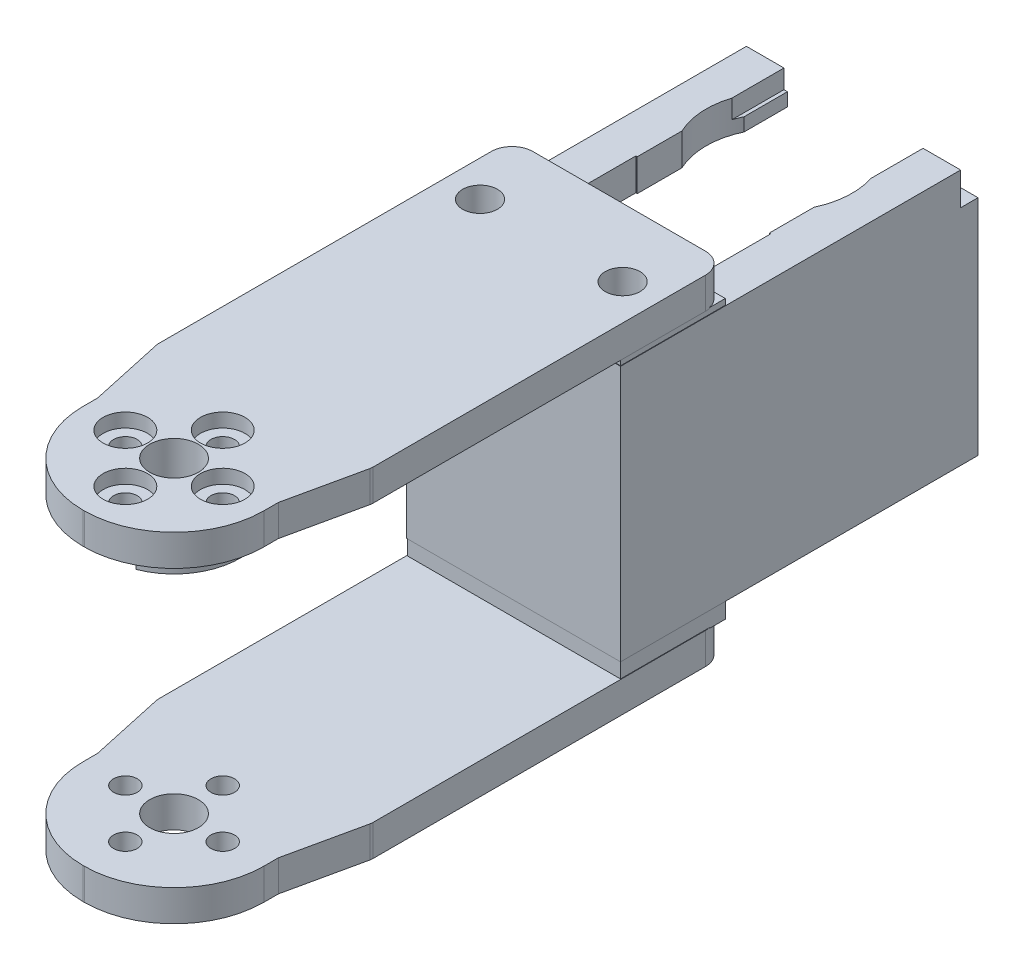
SolidWorks part; units mm, degrees
ref_plane "Front Plane" through (0, 0, 0) normal (0, 0, 1) x (1, 0, 0)
ref_plane "Top Plane" through (0, 0, 0) normal (0, 1, 0) x (1, 0, 0)
ref_plane "Right Plane" through (0, 0, 0) normal (1, 0, 0) x (0, 0, -1)
ref_plane "PY_m23_300" through (0, -23.3, 0) normal (0, 1, 0) x (1, 0, 0)
sketch "S_prism1" plane through (0, -23.3, 0) normal (0, 1, 0) x (1, 0, 0)
  line L0 (-13, 2) -> (-15.354, 12.7893)
  line L1 (-15.4, 13.2156) -> (-15.4, 61)
  line L2 (-12.4, 64) -> (12.4, 64)
  line L3 (15.4, 61) -> (15.4, 13.2156)
  line L4 (15.354, 12.7893) -> (13, 2)
  line L5 (13, 2) -> (13, -0.1)
  line L6 (0.1, -13) -> (-0.1, -13)
  line L7 (-13, -0.1) -> (-13, 2)
  arc A0 (-15.354, 12.7893) -> (-15.4, 13.2156) centre (-13.4076, 13.215) cw
  arc A1 (-15.4, 61) -> (-12.4, 64) centre (-12.3999, 60.9999) cw
  arc A2 (12.4, 64) -> (15.4, 61) centre (12.3999, 60.9999) cw
  arc A3 (15.4, 13.2156) -> (15.354, 12.7893) centre (13.4076, 13.215) cw
  arc A4 (13, -0.1) -> (0.1, -13) centre (0.1001, -0.1001) cw
  arc A5 (-0.1, -13) -> (-13, -0.1) centre (-0.1001, -0.1001) cw
extrude "Boss_1" add sketch "S_prism1" along normal blind 4.5
ref_plane "PY_p17_750" through (0, 17.75, 0) normal (0, 1, 0) x (1, 0, 0)
sketch "S_cyl2" plane through (0, 17.75, 0) normal (0, 1, 0) x (1, 0, 0)
  circle A0 centre (0, 0) radius 9.5
  dimension "D1_S_cyl2" = 19
extrude "Boss_2" add sketch "S_cyl2" along normal blind 3.2
ref_plane "PY_p20_950" through (0, 20.95, 0) normal (0, 1, 0) x (1, 0, 0)
sketch "S_prism3" plane through (0, 20.95, 0) normal (0, 1, 0) x (1, 0, 0)
  line L0 (-13, 2) -> (-15.354, 12.7893)
  line L1 (-15.4, 13.2156) -> (-15.4, 61)
  line L2 (-12.4, 64) -> (12.4, 64)
  line L3 (15.4, 61) -> (15.4, 13.2156)
  line L4 (15.354, 12.7893) -> (13, 2)
  line L5 (13, 2) -> (13, -0.1)
  line L6 (0.1, -13) -> (-0.1, -13)
  line L7 (-13, -0.1) -> (-13, 2)
  arc A0 (-15.354, 12.7893) -> (-15.4, 13.2156) centre (-13.4076, 13.215) cw
  arc A1 (-15.4, 61) -> (-12.4, 64) centre (-12.3999, 60.9999) cw
  arc A2 (12.4, 64) -> (15.4, 61) centre (12.3999, 60.9999) cw
  arc A3 (15.4, 13.2156) -> (15.354, 12.7893) centre (13.4076, 13.215) cw
  arc A4 (13, -0.1) -> (0.1, -13) centre (0.1001, -0.1001) cw
  arc A5 (-0.1, -13) -> (-13, -0.1) centre (-0.1001, -0.1001) cw
extrude "Boss_3" add sketch "S_prism3" along normal blind 4.5
ref_plane "PZ_m51_300" through (0, 0, -51.3) normal (0, 0, 1) x (1, 0, 0)
sketch "S_box4" plane through (0, 0, -51.3) normal (0, 0, 1) x (1, 0, 0)
  line L0 (-15.4, -16.6) -> (15.4, -16.6)
  line L1 (15.4, -16.6) -> (15.4, 20.2)
  line L2 (15.4, 20.2) -> (-15.4, 20.2)
  line L3 (-15.4, 20.2) -> (-15.4, -16.6)
  dimension "P1" = 15.4
  dimension "P2" = 16.6
  dimension "P3" = 15.4
  dimension "P4" = 16.6
  dimension "P5" = 15.4
  dimension "P6" = 20.2
  dimension "P7" = 15.4
  dimension "P8" = 20.2
extrude "Boss_4" add sketch "S_box4" along normal blind 2.5
ref_plane "PZ_m100_200" through (0, 0, -100.2) normal (0, 0, 1) x (1, 0, 0)
sketch "S_box5" plane through (0, 0, -100.2) normal (0, 0, 1) x (1, 0, 0)
  line L0 (12.9, -16.6) -> (15.4, -16.6)
  line L1 (15.4, -16.6) -> (15.4, 20.2)
  line L2 (15.4, 20.2) -> (12.9, 20.2)
  line L3 (12.9, 20.2) -> (12.9, -16.6)
  dimension "P1" = 12.9
  dimension "P2" = 16.6
  dimension "P3" = 15.4
  dimension "P4" = 16.6
  dimension "P5" = 15.4
  dimension "P6" = 20.2
  dimension "P7" = 12.9
  dimension "P8" = 20.2
extrude "Boss_5" add sketch "S_box5" along normal blind 51.4
sketch "S_box6" plane through (0, 0, -100.2) normal (0, 0, 1) x (1, 0, 0)
  line L0 (-15.4, 15.6) -> (15.4, 15.6)
  line L1 (15.4, 15.6) -> (15.4, 20.2)
  line L2 (15.4, 20.2) -> (-15.4, 20.2)
  line L3 (-15.4, 20.2) -> (-15.4, 15.6)
  dimension "P1" = 15.4
  dimension "P2" = 15.6
  dimension "P3" = 15.4
  dimension "P4" = 15.6
  dimension "P5" = 15.4
  dimension "P6" = 20.2
  dimension "P7" = 15.4
  dimension "P8" = 20.2
extrude "Boss_6" add sketch "S_box6" along normal blind 51.4
ref_plane "PZ_m77_000" through (0, 0, -77) normal (0, 0, 1) x (1, 0, 0)
sketch "S_box7" plane through (0, 0, -77) normal (0, 0, 1) x (1, 0, 0)
  line L0 (-15.4, -16.6) -> (-12.9, -16.6)
  line L1 (-12.9, -16.6) -> (-12.9, 20.2)
  line L2 (-12.9, 20.2) -> (-15.4, 20.2)
  line L3 (-15.4, 20.2) -> (-15.4, -16.6)
  dimension "P1" = 15.4
  dimension "P2" = 16.6
  dimension "P3" = 12.9
  dimension "P4" = 16.6
  dimension "P5" = 12.9
  dimension "P6" = 20.2
  dimension "P7" = 15.4
  dimension "P8" = 20.2
extrude "Boss_7" add sketch "S_box7" along normal blind 28.2
ref_plane "PZ_m63_930" through (0, 0, -63.93) normal (0, 0, 1) x (1, 0, 0)
sketch "S_box8" plane through (0, 0, -63.93) normal (0, 0, 1) x (1, 0, 0)
  line L0 (-15.33, -18.9) -> (15.33, -18.9)
  line L1 (15.33, -18.9) -> (15.33, -16.5)
  line L2 (15.33, -16.5) -> (-15.33, -16.5)
  line L3 (-15.33, -16.5) -> (-15.33, -18.9)
  dimension "P1" = 15.33
  dimension "P2" = 18.9
  dimension "P3" = 15.33
  dimension "P4" = 18.9
  dimension "P5" = 15.33
  dimension "P6" = 16.5
  dimension "P7" = 15.33
  dimension "P8" = 16.5
extrude "Boss_8" add sketch "S_box8" along normal blind 15.06
sketch "S_box9" plane through (0, 0, -63.93) normal (0, 0, 1) x (1, 0, 0)
  line L0 (-15.33, 20.1) -> (15.33, 20.1)
  line L1 (15.33, 20.1) -> (15.33, 21.05)
  line L2 (15.33, 21.05) -> (-15.33, 21.05)
  line L3 (-15.33, 21.05) -> (-15.33, 20.1)
  dimension "P1" = 15.33
  dimension "P2" = 20.1
  dimension "P3" = 15.33
  dimension "P4" = 20.1
  dimension "P5" = 15.33
  dimension "P6" = 21.05
  dimension "P7" = 15.33
  dimension "P8" = 21.05
extrude "Boss_9" add sketch "S_box9" along normal blind 15.06
ref_plane "PY_m23_400" through (0, -23.4, 0) normal (0, 1, 0) x (1, 0, 0)
sketch "S_hole10" plane through (0, -23.4, 0) normal (0, 1, 0) x (1, 0, 0)
  circle A0 centre (0, 0) radius 3.5
  dimension "D1_S_hole10" = 7
extrude "Hole_10" cut sketch "S_hole10" along normal blind 4.7
sketch "S_hole11" plane through (0, -23.4, 0) normal (0, 1, 0) x (1, 0, 0)
  circle A0 centre (7, 0) radius 1.7
  dimension "D1_S_hole11" = 3.4
  dimension "P2" = 7
extrude "Hole_11" cut sketch "S_hole11" along normal blind 4.7
sketch "S_hole12" plane through (0, -23.4, 0) normal (0, 1, 0) x (1, 0, 0)
  circle A0 centre (0, -7) radius 1.7
  dimension "D1_S_hole12" = 3.4
  dimension "P2" = 7
extrude "Hole_12" cut sketch "S_hole12" along normal blind 4.7
sketch "S_hole13" plane through (0, -23.4, 0) normal (0, 1, 0) x (1, 0, 0)
  circle A0 centre (-7, 0) radius 1.7
  dimension "D1_S_hole13" = 3.4
  dimension "P2" = 7
extrude "Hole_13" cut sketch "S_hole13" along normal blind 4.7
sketch "S_hole14" plane through (0, -23.4, 0) normal (0, 1, 0) x (1, 0, 0)
  circle A0 centre (0, 7) radius 1.7
  dimension "D1_S_hole14" = 3.4
  dimension "P2" = 7
extrude "Hole_14" cut sketch "S_hole14" along normal blind 4.7
sketch "S_hole15" plane through (0, -23.4, 0) normal (0, 1, 0) x (1, 0, 0)
  circle A0 centre (7, 0) radius 3.2
  dimension "D1_S_hole15" = 6.4
  dimension "P2" = 7
extrude "Hole_15" cut sketch "S_hole15" along normal blind 1.6
sketch "S_hole16" plane through (0, -23.4, 0) normal (0, 1, 0) x (1, 0, 0)
  circle A0 centre (0, -7) radius 3.2
  dimension "D1_S_hole16" = 6.4
  dimension "P2" = 7
extrude "Hole_16" cut sketch "S_hole16" along normal blind 1.6
sketch "S_hole17" plane through (0, -23.4, 0) normal (0, 1, 0) x (1, 0, 0)
  circle A0 centre (-7, 0) radius 3.2
  dimension "D1_S_hole17" = 6.4
  dimension "P2" = 7
extrude "Hole_17" cut sketch "S_hole17" along normal blind 1.6
sketch "S_hole18" plane through (0, -23.4, 0) normal (0, 1, 0) x (1, 0, 0)
  circle A0 centre (0, 7) radius 3.2
  dimension "D1_S_hole18" = 6.4
  dimension "P2" = 7
extrude "Hole_18" cut sketch "S_hole18" along normal blind 1.6
ref_plane "PY_p17_650" through (0, 17.65, 0) normal (0, 1, 0) x (1, 0, 0)
sketch "S_hole19" plane through (0, 17.65, 0) normal (0, 1, 0) x (1, 0, 0)
  circle A0 centre (0, 0) radius 3.5
  dimension "D1_S_hole19" = 7
extrude "Hole_19" cut sketch "S_hole19" along normal blind 7.9
sketch "S_hole20" plane through (0, 17.65, 0) normal (0, 1, 0) x (1, 0, 0)
  circle A0 centre (7, 0) radius 1.7
  dimension "D1_S_hole20" = 3.4
  dimension "P2" = 7
extrude "Hole_20" cut sketch "S_hole20" along normal blind 7.9
sketch "S_hole21" plane through (0, 17.65, 0) normal (0, 1, 0) x (1, 0, 0)
  circle A0 centre (0, -7) radius 1.7
  dimension "D1_S_hole21" = 3.4
  dimension "P2" = 7
extrude "Hole_21" cut sketch "S_hole21" along normal blind 7.9
sketch "S_hole22" plane through (0, 17.65, 0) normal (0, 1, 0) x (1, 0, 0)
  circle A0 centre (-7, 0) radius 1.7
  dimension "D1_S_hole22" = 3.4
  dimension "P2" = 7
extrude "Hole_22" cut sketch "S_hole22" along normal blind 7.9
sketch "S_hole23" plane through (0, 17.65, 0) normal (0, 1, 0) x (1, 0, 0)
  circle A0 centre (0, 7) radius 1.7
  dimension "D1_S_hole23" = 3.4
  dimension "P2" = 7
extrude "Hole_23" cut sketch "S_hole23" along normal blind 7.9
ref_plane "PY_p23_450" through (0, 23.45, 0) normal (0, 1, 0) x (1, 0, 0)
sketch "S_hole24" plane through (0, 23.45, 0) normal (0, 1, 0) x (1, 0, 0)
  circle A0 centre (7, 0) radius 3.2
  dimension "D1_S_hole24" = 6.4
  dimension "P2" = 7
extrude "Hole_24" cut sketch "S_hole24" along normal blind 2.1
sketch "S_hole25" plane through (0, 23.45, 0) normal (0, 1, 0) x (1, 0, 0)
  circle A0 centre (0, -7) radius 3.2
  dimension "D1_S_hole25" = 6.4
  dimension "P2" = 7
extrude "Hole_25" cut sketch "S_hole25" along normal blind 2.1
sketch "S_hole26" plane through (0, 23.45, 0) normal (0, 1, 0) x (1, 0, 0)
  circle A0 centre (-7, 0) radius 3.2
  dimension "D1_S_hole26" = 6.4
  dimension "P2" = 7
extrude "Hole_26" cut sketch "S_hole26" along normal blind 2.1
sketch "S_hole27" plane through (0, 23.45, 0) normal (0, 1, 0) x (1, 0, 0)
  circle A0 centre (0, 7) radius 3.2
  dimension "D1_S_hole27" = 6.4
  dimension "P2" = 7
extrude "Hole_27" cut sketch "S_hole27" along normal blind 2.1
sketch "S_cut28" plane through (0, 0, 0) normal (0, 0, 1) x (1, 0, 0)
  line L0 (-3.4, 17.65) -> (3.4, 17.65)
  line L1 (3.4, 17.65) -> (3.4, 18.65)
  line L2 (3.4, 18.65) -> (-3.4, 18.65)
  line L3 (-3.4, 18.65) -> (-3.4, 17.65)
  dimension "P1" = 3.4
  dimension "P2" = 17.65
  dimension "P3" = 3.4
  dimension "P4" = 17.65
  dimension "P5" = 3.4
  dimension "P6" = 18.65
  dimension "P7" = 3.4
  dimension "P8" = 18.65
extrude "Pocket_28" cut sketch "S_cut28" along normal blind 10
ref_plane "PY_p15_500" through (0, 15.5, 0) normal (0, 1, 0) x (1, 0, 0)
sketch "S_hole29" plane through (0, 15.5, 0) normal (0, 1, 0) x (1, 0, 0)
  circle A0 centre (0, 87) radius 10.5
  dimension "D1_S_hole29" = 21
  dimension "P2" = 87
extrude "Hole_29" cut sketch "S_hole29" along normal blind 4.8
ref_plane "PZ_m76_100" through (0, 0, -76.1) normal (0, 0, 1) x (1, 0, 0)
sketch "S_cut30" plane through (0, 0, -76.1) normal (0, 0, 1) x (1, 0, 0)
  line L0 (-9.7, 15.55) -> (9.7, 15.55)
  line L1 (9.7, 15.55) -> (9.7, 20.3)
  line L2 (9.7, 20.3) -> (-9.7, 20.3)
  line L3 (-9.7, 20.3) -> (-9.7, 15.55)
  dimension "P1" = 9.7
  dimension "P2" = 15.55
  dimension "P3" = 9.7
  dimension "P4" = 15.55
  dimension "P5" = 9.7
  dimension "P6" = 20.3
  dimension "P7" = 9.7
  dimension "P8" = 20.3
extrude "Pocket_30" cut sketch "S_cut30" along normal blind 19.5
ref_plane "PZ_m56_600" through (0, 0, -56.6) normal (0, 0, 1) x (1, 0, 0)
sketch "S_cut31" plane through (0, 0, -56.6) normal (0, 0, 1) x (1, 0, 0)
  line L0 (-8.2, 15.55) -> (8.2, 15.55)
  line L1 (8.2, 15.55) -> (8.2, 20.3)
  line L2 (8.2, 20.3) -> (-8.2, 20.3)
  line L3 (-8.2, 20.3) -> (-8.2, 15.55)
  dimension "P1" = 8.2
  dimension "P2" = 15.55
  dimension "P3" = 8.2
  dimension "P4" = 15.55
  dimension "P5" = 8.2
  dimension "P6" = 20.3
  dimension "P7" = 8.2
  dimension "P8" = 20.3
extrude "Pocket_31" cut sketch "S_cut31" along normal blind 8.3
ref_plane "PZ_m87_000" through (0, 0, -87) normal (0, 0, 1) x (1, 0, 0)
sketch "S_cut32" plane through (0, 0, -87) normal (0, 0, 1) x (1, 0, 0)
  line L0 (-3.5, 15.55) -> (3.5, 15.55)
  line L1 (3.5, 15.55) -> (3.5, 20.3)
  line L2 (3.5, 20.3) -> (-3.5, 20.3)
  line L3 (-3.5, 20.3) -> (-3.5, 15.55)
  dimension "P1" = 3.5
  dimension "P2" = 15.55
  dimension "P3" = 3.5
  dimension "P4" = 15.55
  dimension "P5" = 3.5
  dimension "P6" = 20.3
  dimension "P7" = 3.5
  dimension "P8" = 20.3
extrude "Pocket_32" cut sketch "S_cut32" along normal blind 11
ref_plane "PZ_m100_700" through (0, 0, -100.7) normal (0, 0, 1) x (1, 0, 0)
sketch "S_cut33" plane through (0, 0, -100.7) normal (0, 0, 1) x (1, 0, 0)
  line L0 (-10, 17.5) -> (10, 17.5)
  line L1 (10, 17.5) -> (10, 20.4)
  line L2 (10, 20.4) -> (-10, 20.4)
  line L3 (-10, 20.4) -> (-10, 17.5)
  dimension "P1" = 10
  dimension "P2" = 17.5
  dimension "P3" = 10
  dimension "P4" = 17.5
  dimension "P5" = 10
  dimension "P6" = 20.4
  dimension "P7" = 10
  dimension "P8" = 20.4
extrude "Pocket_33" cut sketch "S_cut33" along normal blind 13.7
sketch "S_hole34" plane through (0, 15.5, 0) normal (0, 1, 0) x (1, 0, 0)
  circle A0 centre (-10.25, 54.25) radius 1.1
  dimension "D1_S_hole34" = 2.2
  dimension "P2" = 10.25
  dimension "P3" = 54.25
extrude "Hole_34" cut sketch "S_hole34" along normal blind 4.8
ref_plane "PY_p18_600" through (0, 18.6, 0) normal (0, 1, 0) x (1, 0, 0)
sketch "S_hole35" plane through (0, 18.6, 0) normal (0, 1, 0) x (1, 0, 0)
  circle A0 centre (-10.25, 54.25) radius 2.3
  dimension "D1_S_hole35" = 4.6
  dimension "P2" = 10.25
  dimension "P3" = 54.25
extrude "Hole_35" cut sketch "S_hole35" along normal blind 1.7
sketch "S_hole36" plane through (0, 15.5, 0) normal (0, 1, 0) x (1, 0, 0)
  circle A0 centre (10.25, 54.25) radius 1.1
  dimension "D1_S_hole36" = 2.2
  dimension "P2" = 10.25
  dimension "P3" = 54.25
extrude "Hole_36" cut sketch "S_hole36" along normal blind 4.8
sketch "S_hole37" plane through (0, 18.6, 0) normal (0, 1, 0) x (1, 0, 0)
  circle A0 centre (10.25, 54.25) radius 2.3
  dimension "D1_S_hole37" = 4.6
  dimension "P2" = 10.25
  dimension "P3" = 54.25
extrude "Hole_37" cut sketch "S_hole37" along normal blind 1.7
ref_plane "PZ_m100_300" through (0, 0, -100.3) normal (0, 0, 1) x (1, 0, 0)
sketch "S_cut38" plane through (0, 0, -100.3) normal (0, 0, 1) x (1, 0, 0)
  line L0 (-15.5, 15.5) -> (15.5, 15.5)
  line L1 (15.5, 15.5) -> (15.5, 20.3)
  line L2 (15.5, 20.3) -> (-15.5, 20.3)
  line L3 (-15.5, 20.3) -> (-15.5, 15.5)
  dimension "P1" = 15.5
  dimension "P2" = 15.5
  dimension "P3" = 15.5
  dimension "P4" = 15.5
  dimension "P5" = 15.5
  dimension "P6" = 20.3
  dimension "P7" = 15.5
  dimension "P8" = 20.3
extrude "Pocket_38" cut sketch "S_cut38" along normal blind 2.6
ref_plane "PZ_m97_800" through (0, 0, -97.8) normal (0, 0, 1) x (1, 0, 0)
sketch "S_cut39" plane through (0, 0, -97.8) normal (0, 0, 1) x (1, 0, 0)
  line L0 (-9.5, 15.55) -> (9.5, 15.55)
  line L1 (9.5, 15.55) -> (9.5, 20.3)
  line L2 (9.5, 20.3) -> (-9.5, 20.3)
  line L3 (-9.5, 20.3) -> (-9.5, 15.55)
  dimension "P1" = 9.5
  dimension "P2" = 15.55
  dimension "P3" = 9.5
  dimension "P4" = 15.55
  dimension "P5" = 9.5
  dimension "P6" = 20.3
  dimension "P7" = 9.5
  dimension "P8" = 20.3
extrude "Pocket_39" cut sketch "S_cut39" along normal blind 22.2
ref_plane "PZ_m78_900" through (0, 0, -78.9) normal (0, 0, 1) x (1, 0, 0)
sketch "S_cut40" plane through (0, 0, -78.9) normal (0, 0, 1) x (1, 0, 0)
  line L0 (-7.5, -17.75) -> (7.5, -17.75)
  line L1 (7.5, -17.75) -> (7.5, -16.2)
  line L2 (7.5, -16.2) -> (-7.5, -16.2)
  line L3 (-7.5, -16.2) -> (-7.5, -17.75)
  dimension "P1" = 7.5
  dimension "P2" = 17.75
  dimension "P3" = 7.5
  dimension "P4" = 17.75
  dimension "P5" = 7.5
  dimension "P6" = 16.2
  dimension "P7" = 7.5
  dimension "P8" = 16.2
extrude "Pocket_40" cut sketch "S_cut40" along normal blind 27.4
ref_plane "PY_p20_250" through (0, 20.25, 0) normal (0, 1, 0) x (1, 0, 0)
sketch "S_hole41" plane through (0, 20.25, 0) normal (0, 1, 0) x (1, 0, 0)
  circle A0 centre (-10.25, 54.25) radius 2.5
  dimension "D1_S_hole41" = 5
  dimension "P2" = 10.25
  dimension "P3" = 54.25
extrude "Hole_41" cut sketch "S_hole41" along normal blind 5.3
sketch "S_hole42" plane through (0, 20.25, 0) normal (0, 1, 0) x (1, 0, 0)
  circle A0 centre (10.25, 54.25) radius 2.5
  dimension "D1_S_hole42" = 5
  dimension "P2" = 10.25
  dimension "P3" = 54.25
extrude "Hole_42" cut sketch "S_hole42" along normal blind 5.3
equation "\"plate_t\" = 3"
equation "\"clearance\" = 0.5"
